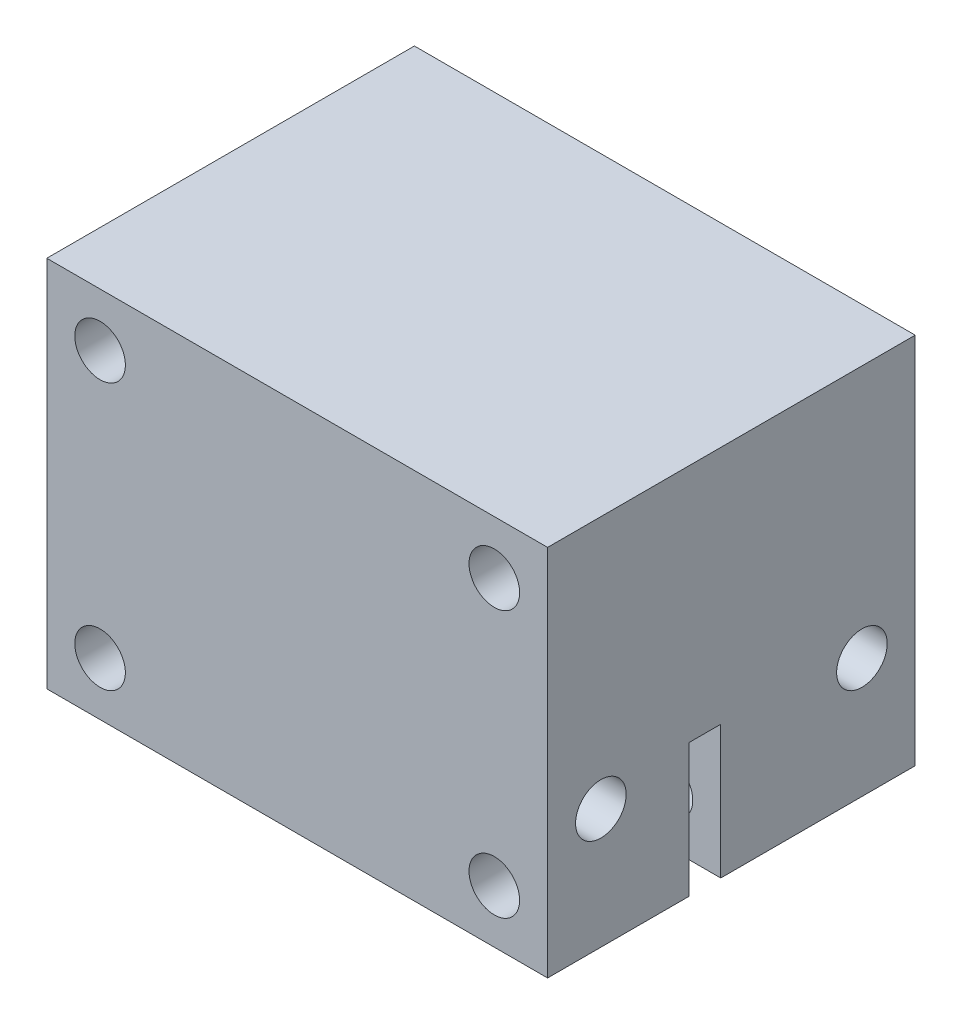
SolidWorks part; units mm, degrees
material "ABS"
ref_plane "前视基准面" through (0, 0, 0) normal (0, 0, 1) x (1, 0, 0)
ref_plane "上视基准面" through (0, 0, 0) normal (0, 1, 0) x (1, 0, 0)
ref_plane "右视基准面" through (0, 0, 0) normal (1, 0, 0) x (0, 0, -1)
sketch "草图1" plane through (0, 0, 0) normal (0, 0, 1) x (1, 0, 0)
  line L0 (18.8, 28) -> (18.8, 0) construction
  line L1 (0, 0) -> (37.6, 0)
  line L2 (0, 0) -> (0, 28)
  line L3 (0, 28) -> (37.6, 28)
  line L4 (37.6, 0) -> (37.6, 28)
  line L6 (4, 4) -> (33.6, 4) construction
  line L7 (4, 4) -> (4, 24) construction
  line L8 (4, 24) -> (33.6, 24) construction
  line L9 (33.6, 4) -> (33.6, 24) construction
  line L10 (4, 4) -> (33.6, 24) construction
  line L11 (4, 24) -> (33.6, 4) construction
  circle A0 centre (4, 24) radius 1.9
  circle A1 centre (33.6, 24) radius 1.9
  circle A2 centre (33.6, 4) radius 1.9
  circle A3 centre (4, 4) radius 1.9
  point P7 (18.8, 14)
  dimension "D3" = 20
  dimension "D5" = 3.8
  dimension "D1" = 28
  dimension "D2" = 37.6
  dimension "D4" = 29.6
extrude "凸台-拉伸1" add sketch "草图1" along normal blind 27.6
sketch "草图2" plane through (37.6, 0, 0) normal (1, 0, 0) x (0, 0, -1)
  line L0 (-13.8, 28) -> (-13.8, 0) construction
  line L1 (-27.6, 28) -> (0, 28) construction
  line L2 (-27.6, 0) -> (0, 0) construction
  line L3 (-23.6, 9) -> (-4, 9) construction
  line L4 (-27.6, 0) -> (-27.6, 28) construction
  line L5 (-17, 0) -> (-14.6, 0)
  line L6 (-17, 0) -> (-17, 10)
  line L7 (-17, 10) -> (-14.6, 10)
  line L8 (-14.6, 0) -> (-14.6, 10)
  circle A0 centre (-23.6, 9) radius 1.9
  circle A1 centre (-4, 9) radius 1.9
  point P8 (-13.8, 9)
  dimension "D3" = 3.8
  dimension "D1" = 9
  dimension "D2" = 4
  dimension "D4" = 2.4
  dimension "D5" = 10.6
  dimension "D6" = 10
extrude "切除-拉伸1" cut sketch "草图2" against normal through all
